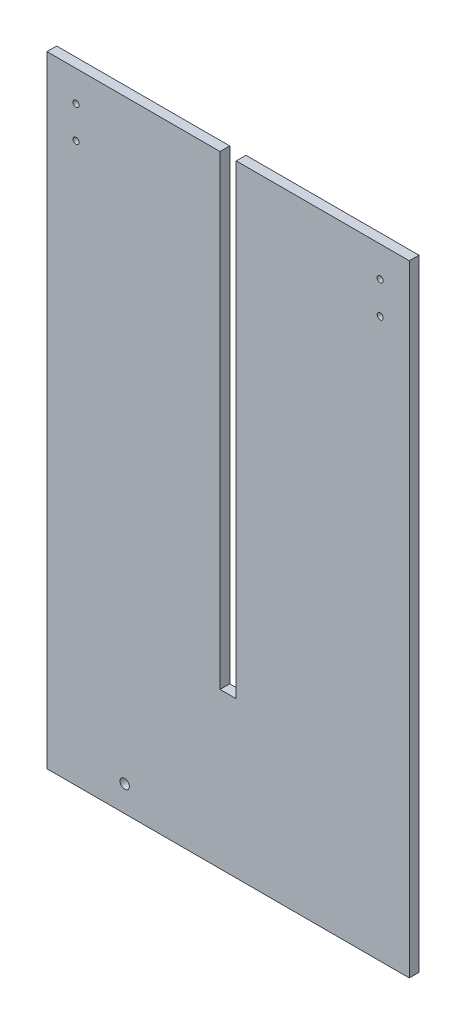
SolidWorks part; units mm, degrees
ref_plane "Front Plane" through (0, 0, 0) normal (0, 0, 1) x (1, 0, 0)
ref_plane "Top Plane" through (0, 0, 0) normal (0, 1, 0) x (1, 0, 0)
ref_plane "Right Plane" through (0, 0, 0) normal (1, 0, 0) x (0, 0, -1)
sketch "Sketch2" plane through (0, 0, 0) normal (0, 0, 1) x (1, 0, 0)
  line L0 (0, 152.4) -> (0, -152.4) construction
  line L1 (-88.9, 152.4) -> (88.9, 152.4)
  line L2 (-88.9, 152.4) -> (-88.9, -152.4)
  line L3 (-88.9, -152.4) -> (88.9, -152.4)
  line L4 (88.9, 152.4) -> (88.9, -152.4)
  line L5 (-88.9, 108.1768) -> (-88.9, 63.9536)
  line L6 (-88.9, 152.4) -> (-93.6625, 152.4)
  line L7 (-88.9, 152.4) -> (-88.9, 108.1768)
  line L8 (-88.9, 108.1768) -> (-93.6625, 108.1768)
  line L9 (-93.6625, 152.4) -> (-93.6625, 108.1768)
  line L10 (88.9, 152.4) -> (93.6625, 152.4)
  line L11 (88.9, 152.4) -> (88.9, 108.1768)
  line L12 (88.9, 108.1768) -> (93.6625, 108.1768)
  line L13 (93.6625, 152.4) -> (93.6625, 108.1768)
  line L14 (-66.9018, -152.4) -> (-93.6625, -152.4)
  line L15 (-66.9018, -152.4) -> (-66.9018, -157.1625)
  line L16 (-66.9018, -157.1625) -> (-93.6625, -157.1625)
  line L17 (-93.6625, -152.4) -> (-93.6625, -157.1625)
  line L18 (-88.9, 108.1768) -> (-93.6625, 108.1768)
  line L19 (-93.6625, 108.1768) -> (-93.6625, 63.9536)
  line L20 (-88.9, 63.9536) -> (-93.6625, 63.9536)
  line L21 (88.9, 108.1768) -> (88.9, 63.9536)
  line L22 (88.9, 108.1768) -> (93.6625, 108.1768)
  line L23 (93.6625, 108.1768) -> (93.6625, 63.9536)
  line L24 (88.9, 63.9536) -> (93.6625, 63.9536)
  line L25 (-88.9, 63.9536) -> (-88.9, 19.7304)
  line L26 (-88.9, 63.9536) -> (-93.6625, 63.9536)
  line L27 (-93.6625, 63.9536) -> (-93.6625, 19.7304)
  line L28 (-88.9, 19.7304) -> (-93.6625, 19.7304)
  line L29 (88.9, 63.9536) -> (88.9, 19.7304)
  line L30 (88.9, 63.9536) -> (93.6625, 63.9536)
  line L31 (93.6625, 63.9536) -> (93.6625, 19.7304)
  line L32 (88.9, 19.7304) -> (93.6625, 19.7304)
  line L33 (-88.9, 19.7304) -> (-88.9, -24.4929)
  line L34 (-88.9, 19.7304) -> (-93.6625, 19.7304)
  line L35 (-93.6625, 19.7304) -> (-93.6625, -24.4929)
  line L36 (-88.9, -24.4929) -> (-93.6625, -24.4929)
  line L37 (88.9, 19.7304) -> (88.9, -24.4929)
  line L38 (88.9, 19.7304) -> (93.6625, 19.7304)
  line L39 (93.6625, 19.7304) -> (93.6625, -24.4929)
  line L40 (88.9, -24.4929) -> (93.6625, -24.4929)
  line L41 (-88.9, -24.4929) -> (-88.9, -68.7161)
  line L42 (-88.9, -24.4929) -> (-93.6625, -24.4929)
  line L43 (-93.6625, -24.4929) -> (-93.6625, -68.7161)
  line L44 (-88.9, -68.7161) -> (-93.6625, -68.7161)
  line L45 (88.9, -24.4929) -> (88.9, -68.7161)
  line L46 (88.9, -24.4929) -> (93.6625, -24.4929)
  line L47 (93.6625, -24.4929) -> (93.6625, -68.7161)
  line L48 (88.9, -68.7161) -> (93.6625, -68.7161)
  line L49 (-88.9, -68.7161) -> (-88.9, -112.9393)
  line L50 (-88.9, -68.7161) -> (-93.6625, -68.7161)
  line L51 (-93.6625, -68.7161) -> (-93.6625, -112.9393)
  line L52 (-88.9, -112.9393) -> (-93.6625, -112.9393)
  line L53 (88.9, -68.7161) -> (88.9, -112.9393)
  line L54 (88.9, -68.7161) -> (93.6625, -68.7161)
  line L55 (93.6625, -68.7161) -> (93.6625, -112.9393)
  line L56 (88.9, -112.9393) -> (93.6625, -112.9393)
  line L57 (-88.9, -112.9393) -> (-88.9, -157.1625)
  line L58 (-88.9, -112.9393) -> (-93.6625, -112.9393)
  line L59 (-93.6625, -112.9393) -> (-93.6625, -157.1625)
  line L60 (-88.9, -157.1625) -> (-93.6625, -157.1625)
  line L61 (88.9, -112.9393) -> (88.9, -157.1625)
  line L62 (88.9, -112.9393) -> (93.6625, -112.9393)
  line L63 (93.6625, -112.9393) -> (93.6625, -157.1625)
  line L64 (88.9, -157.1625) -> (93.6625, -157.1625)
  line L65 (-40.1411, -152.4) -> (-40.1411, -157.1625)
  line L66 (-40.1411, -152.4) -> (-66.9018, -152.4)
  line L67 (-66.9018, -152.4) -> (-66.9018, -157.1625)
  line L68 (-40.1411, -157.1625) -> (-66.9018, -157.1625)
  line L69 (-13.3804, -152.4) -> (-13.3804, -157.1625)
  line L70 (-13.3804, -152.4) -> (-40.1411, -152.4)
  line L71 (-40.1411, -152.4) -> (-40.1411, -157.1625)
  line L72 (-13.3804, -157.1625) -> (-40.1411, -157.1625)
  line L73 (13.3804, -152.4) -> (13.3804, -157.1625)
  line L74 (13.3804, -152.4) -> (-13.3804, -152.4)
  line L75 (-13.3804, -152.4) -> (-13.3804, -157.1625)
  line L76 (13.3804, -157.1625) -> (-13.3804, -157.1625)
  line L77 (40.1411, -152.4) -> (40.1411, -157.1625)
  line L78 (40.1411, -152.4) -> (13.3804, -152.4)
  line L79 (13.3804, -152.4) -> (13.3804, -157.1625)
  line L80 (40.1411, -157.1625) -> (13.3804, -157.1625)
  line L81 (66.9018, -152.4) -> (66.9018, -157.1625)
  line L82 (66.9018, -152.4) -> (40.1411, -152.4)
  line L83 (40.1411, -152.4) -> (40.1411, -157.1625)
  line L84 (66.9018, -157.1625) -> (40.1411, -157.1625)
  line L85 (93.6625, -152.4) -> (93.6625, -157.1625)
  line L86 (93.6625, -152.4) -> (66.9018, -152.4)
  line L87 (66.9018, -152.4) -> (66.9018, -157.1625)
  line L88 (93.6625, -157.1625) -> (66.9018, -157.1625)
  point P6 (0, 0)
  dimension "D1" = 177.8
  dimension "D2" = 187.325
  dimension "D3" = 304.8
  dimension "D4" = 309.5625
  dimension "D6" = 44.2232
  dimension "D8" = 26.7607
  dimension "D5" = 7
  dimension "D7" = 7
extrude "Boss-Extrude1" add sketch "Sketch2" along normal blind 4.7625 contours L0 L1 L2 L3 | L1 L0 L3 L4 | L20 L2 L8 L19 | L36 L2 L28 L35 | L52 L2 L44 L51 | L3 L57 L16 L15 | L72 L69 L3 L65 | L80 L77 L3 L73 | L4 L56 L55 L48 | L4 L40 L39 L32 | L4 L24 L23 L12 | L88 L61 L3 L81
sketch "Sketch3" plane through (0, 0, 4.7625) normal (0, 0, 1) x (1, 0, 0)
  line L0 (-88.9, 152.4) -> (88.9, 152.4) construction
  line L1 (-3.9688, 152.4) -> (3.9687, 152.4)
  line L2 (-3.9688, 152.4) -> (-3.9687, -76.2)
  line L3 (-3.9687, -76.2) -> (3.9688, -76.2)
  line L4 (3.9687, 152.4) -> (3.9688, -76.2)
  line L5 (0, -76.2) -> (0, 0) construction
  dimension "D1" = 7.9375
  dimension "D2" = 228.6
extrude "Cut-Extrude1" cut sketch "Sketch3" against normal through all
sketch "Sketch4" plane through (0, 0, 4.7625) normal (0, 0, 1) x (1, 0, 0)
  line L0 (-66.9018, -152.4) -> (-40.1411, -152.4) construction
  line L1 (-88.9, -112.9393) -> (-88.9, -157.1625) construction
  circle A0 centre (-50.8, -139.7) radius 2.3
  dimension "D1" = 4.6
  dimension "D2" = 12.7
  dimension "D3" = 38.1
extrude "Cut-Extrude2" cut sketch "Sketch4" against normal through all
sketch "Sketch5" plane through (0, 0, 4.7625) normal (0, 0, 1) x (1, 0, 0)
  line L0 (0, -152.4) -> (0, 152.4) construction
  line L1 (-13.3804, -152.4) -> (13.3804, -152.4) construction
  line L2 (3.9687, 152.4) -> (88.9, 152.4) construction
  line L3 (-88.9, 152.4) -> (-3.9688, 152.4) construction
  line L5 (-93.6625, 108.1768) -> (-93.6625, 63.9536) construction
  circle A0 centre (-74.6125, 137.4) radius 1.5
  circle A1 centre (-74.6125, 121.65) radius 1.5
  circle A2 centre (74.6125, 121.65) radius 1.5
  circle A3 centre (74.6125, 137.4) radius 1.5
  dimension "D1" = 15.75
  dimension "D2" = 15
  dimension "D4" = 3
  dimension "D5" = 3
  dimension "D3" = 19.05
extrude "Cut-Extrude3" cut sketch "Sketch5" against normal up to surface (4.7625 mm away) up to face at (-48.5, -139.7, 0)
sketch "Sketch6" plane through (0, 0, 4.7625) normal (0, 0, 1) x (1, 0, 0)
  line L1 (-93.6625, 63.9536) -> (-88.9, 63.9536)
  line L2 (-93.6625, 63.9536) -> (-93.6625, 19.7304)
  line L3 (-93.6625, 19.7304) -> (-88.9, 19.7304)
  line L4 (-88.9, 63.9536) -> (-88.9, 19.7304)
  line L5 (-93.6625, -24.4929) -> (-88.9, -24.4929)
  line L6 (-93.6625, -24.4929) -> (-93.6625, -68.7161)
  line L7 (-93.6625, -68.7161) -> (-88.9, -68.7161)
  line L8 (-88.9, -24.4929) -> (-88.9, -68.7161)
  line L9 (93.6625, 63.9536) -> (88.9, 63.9536)
  line L10 (93.6625, 63.9536) -> (93.6625, 19.7304)
  line L11 (93.6625, 19.7304) -> (88.9, 19.7304)
  line L12 (88.9, 63.9536) -> (88.9, 19.7304)
  line L13 (88.9, -24.4929) -> (93.6625, -24.4929)
  line L14 (88.9, -24.4929) -> (88.9, -68.7161)
  line L15 (88.9, -68.7161) -> (93.6625, -68.7161)
  line L16 (93.6625, -24.4929) -> (93.6625, -68.7161)
extrude "Boss-Extrude2" add sketch "Sketch6" against normal up to surface (4.7625 mm away) up to face at (76.1125, 137.4, 0)
sketch "Sketch7" plane through (0, 0, 4.7625) normal (0, 0, 1) x (1, 0, 0)
  line L1 (-40.1411, -152.4) -> (-13.3804, -152.4)
  line L2 (-40.1411, -152.4) -> (-40.1411, -157.1625)
  line L3 (-40.1411, -157.1625) -> (-13.3804, -157.1625)
  line L4 (-13.3804, -152.4) -> (-13.3804, -157.1625)
  line L5 (13.3804, -152.4) -> (40.1411, -152.4)
  line L6 (13.3804, -152.4) -> (13.3804, -157.1625)
  line L7 (13.3804, -157.1625) -> (40.1411, -157.1625)
  line L8 (40.1411, -152.4) -> (40.1411, -157.1625)
extrude "Cut-Extrude4" cut sketch "Sketch7" against normal up to surface (4.7625 mm away) up to face at (0, -61.9125, 0)
sketch "Sketch9" plane through (0, 0, 0) normal (0, 0, -1) x (-1, 0, 0)
  line L0 (-88.9, 108.1768) -> (-88.9, -112.9393)
  line L1 (-88.9, -112.9393) -> (-93.6625, -112.9393)
  line L2 (-93.6625, -112.9393) -> (-93.6625, 108.1768)
  line L3 (-93.6625, 108.1768) -> (-88.9, 108.1768)
  line L4 (88.9, 108.1768) -> (88.9, -112.9393)
  line L5 (88.9, -112.9393) -> (93.6625, -112.9393)
  line L6 (93.6625, -112.9393) -> (93.6625, 108.1768)
  line L7 (93.6625, 108.1768) -> (88.9, 108.1768)
  line L9 (-66.9018, -152.4) -> (-88.9, -152.4)
  line L10 (-66.9018, -152.4) -> (-66.9018, -157.1625)
  line L11 (-66.9018, -157.1625) -> (-88.9, -157.1625)
  line L12 (-88.9, -152.4) -> (-88.9, -157.1625)
  line L13 (66.9018, -152.4) -> (88.9, -152.4)
  line L14 (66.9018, -152.4) -> (66.9018, -157.1625)
  line L15 (66.9018, -157.1625) -> (88.9, -157.1625)
  line L16 (88.9, -152.4) -> (88.9, -157.1625)
extrude "Cut-Extrude5" cut sketch "Sketch9" against normal up to surface (4.7625 mm away) up to face at (0, -24.765, 4.7625)
equation "\"Height\"= 12in"
equation "\"Depth\"= 7in"
equation "\"WallThickness\"= 0.1875in"
equation "\"FloorThickness\"= 0.1875in"
equation "\"D1@Sketch2\"=\"Depth\""
equation "\"D2@Sketch2\"=\"D1@Sketch2\"+2*\"WallThickness\""
equation "\"D3@Sketch2\"=\"Height\""
equation "\"D4@Sketch2\"=\"D3@Sketch2\"+\"FloorThickness\""
equation "\"D6@Sketch2\"=\"D4@Sketch2\"/\"D5@Sketch2\""
equation "\"D8@Sketch2\"=\"D2@Sketch2\"/\"D7@Sketch2\""
equation "\"D1@Boss-Extrude1\"=\"WallThickness\""
equation "\"Width\" = 30in"
